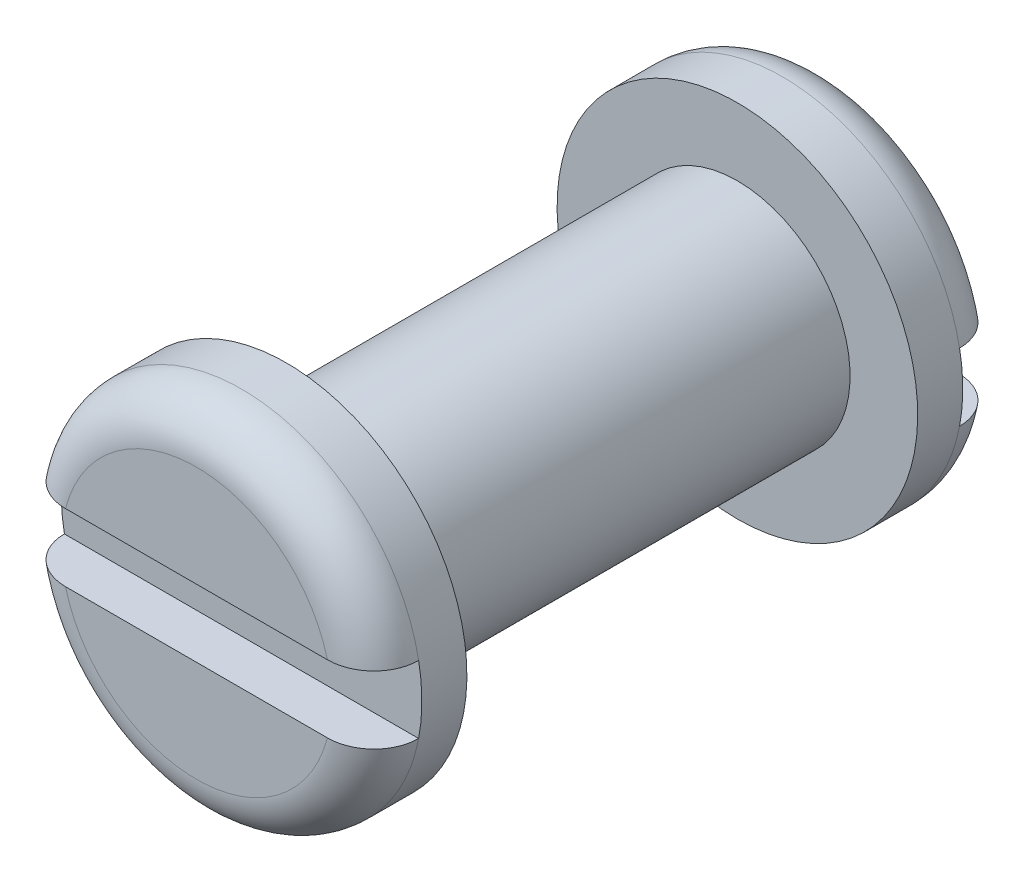
SolidWorks part; units mm, degrees
material "AISI 1045 Steel, cold drawn"
ref_plane "Front Plane" through (0, 0, 0) normal (1, 0, 0) x (0, 1, 0)
ref_plane "Top Plane" through (0, 0, 0) normal (0, 0, 1) x (0, 1, 0)
ref_plane "Right Plane" through (0, 0, 0) normal (0, 1, 0) x (-1, 0, 0)
sketch "Sketch1" plane through (0, 0, 0) normal (1, 0, 0) x (0, 1, 0)
  line L0 (0, 9.3184) -> (0, -10.5587) construction
  line L1 (-6.9513, 0) -> (8.1291, 0) construction
  line L4 (0, 7) -> (3, 7)
  line L5 (4, 6) -> (4, 5)
  line L6 (4, 5) -> (2.5, 5)
  line L7 (2.5, 5) -> (2.5, -5)
  line L10 (0, -7) -> (3, -7)
  line L11 (4, -6) -> (4, -5)
  line L12 (4, -5) -> (2.5, -5)
  line L13 (0, 7) -> (0, -7)
  arc A0 (3, -7) -> (4, -6) centre (3, -6) ccw
  arc A1 (3, 7) -> (4, 6) centre (3, 6) cw
  point P14 (4, -7)
  point P18 (2.5, 0)
  point P21 (4, 7)
  dimension "D4" = 1
  dimension "D1" = 5
  dimension "D2" = 10
  dimension "D3" = 2
  dimension "D5" = 8
revolve "Revolve1" add sketch "Sketch1" angle 360 about L0
sketch "Sketch3" plane through (0, 0, 0) normal (1, 0, 0) x (0, 1, 0)
  line L0 (-5.7834, 0) -> (6.3673, 0) construction
  line L1 (3, 7) -> (-3, 7) construction
  line L2 (-0.75, 7) -> (0.75, 7)
  line L3 (-0.75, 7) -> (-0.75, 6)
  line L4 (-0.75, 6) -> (0.75, 6)
  line L5 (0.75, 7) -> (0.75, 6)
  line L6 (-0.75, -6) -> (0.75, -6)
  line L7 (0.75, -7) -> (0.75, -6)
  line L8 (-0.75, -7) -> (0.75, -7)
  line L9 (-0.75, -7) -> (-0.75, -6)
  point P7 (0, 7)
  dimension "D1" = 1.5
  dimension "D2" = 1
extrude "Cut-Extrude1" cut sketch "Sketch3" against normal through all both and the other way through all
